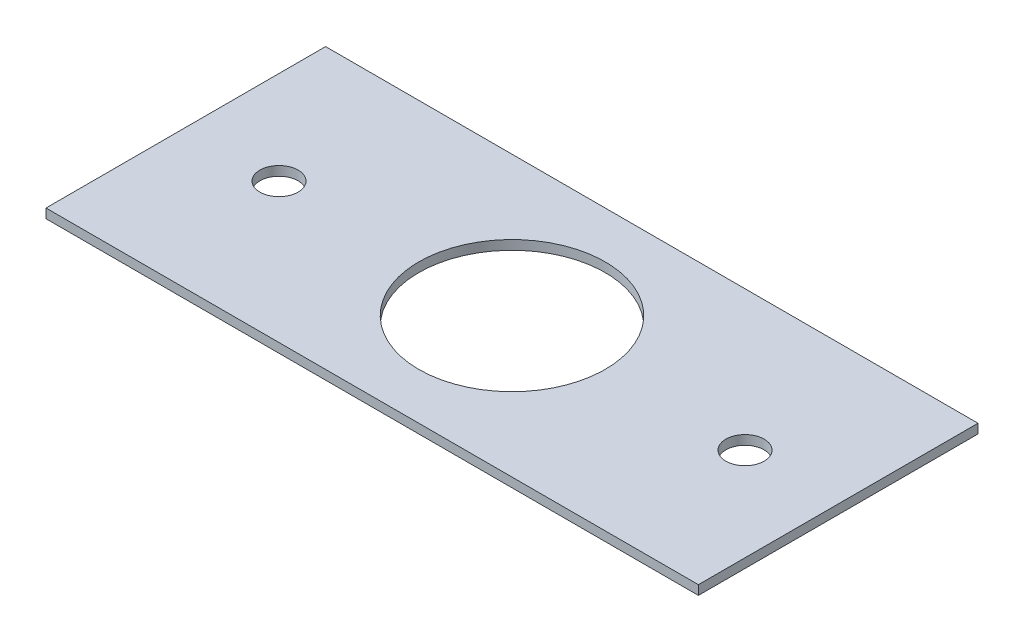
SolidWorks part; units mm, degrees
ref_plane "Front Plane" through (0, 0, 0) normal (0, 0, 1) x (1, 0, 0)
ref_plane "Top Plane" through (0, 0, 0) normal (0, 1, 0) x (1, 0, 0)
ref_plane "Right Plane" through (0, 0, 0) normal (1, 0, 0) x (0, 0, -1)
sketch "Sketch1" plane through (0, 0, 0) normal (0, 1, 0) x (1, 0, 0)
  line L0 (-35, 0) -> (35, 0) construction
  line L1 (-35, 15) -> (35, 15)
  line L2 (-35, 15) -> (-35, -15)
  line L3 (-35, -15) -> (35, -15)
  line L4 (35, 15) -> (35, -15)
  line L5 (-35, 15) -> (35, -15) construction
  line L6 (-35, -15) -> (35, 15) construction
  circle A0 centre (0, 0) radius 10
  circle A1 centre (-25, 0) radius 2.05
  circle A2 centre (25, 0) radius 2.05
  dimension "D1" = 20
  dimension "D6" = 4.1
  dimension "D2" = 30
  dimension "D3" = 70
  dimension "D4" = 25
  dimension "D5" = 25
extrude "Boss-Extrude1" add sketch "Sketch1" along normal blind 1
